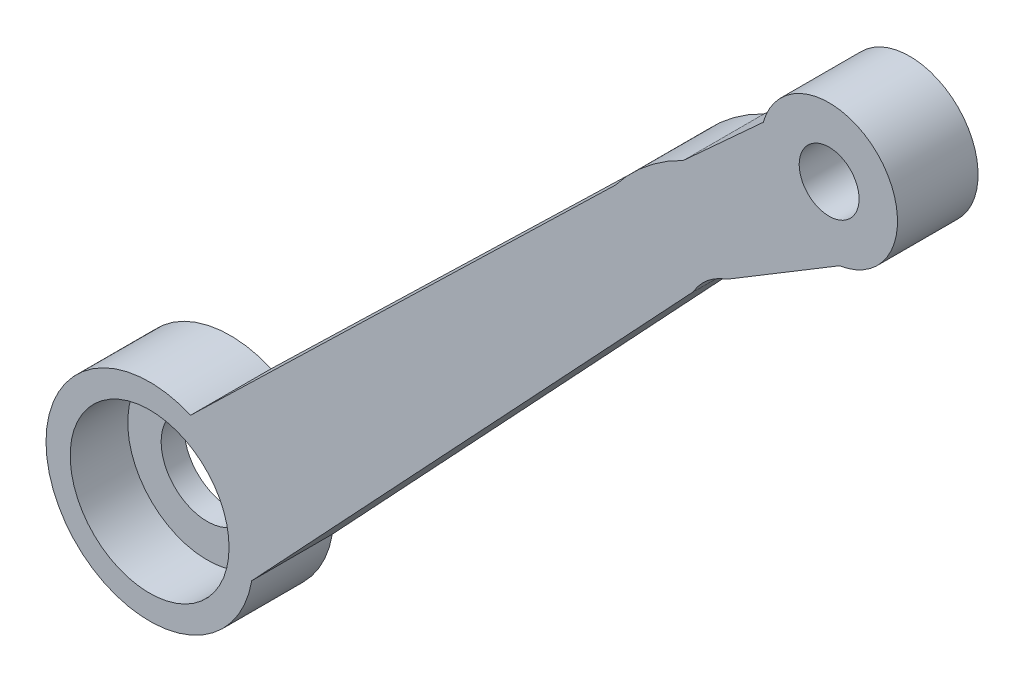
SolidWorks part; units mm, degrees
ref_plane "Front Plane" through (0, 0, 0) normal (0, 0, 1) x (1, 0, 0)
ref_plane "Top Plane" through (0, 0, 0) normal (0, 1, 0) x (1, 0, 0)
ref_plane "Right Plane" through (0, 0, 0) normal (1, 0, 0) x (0, 0, -1)
sketch "Sketch1" plane through (0, 0, 0) normal (0, 0, 1) x (1, 0, 0)
  line L8 (-116.1165, -73.1162) -> (-77.7804, -32.2217)
  line L9 (-74.8335, -29.7976) -> (-65.0583, -23.8962)
  line L10 (-71.6872, -16.4176) -> (-78.6359, -22.7631)
  line L11 (-84.5297, -27.5637) -> (-121.4306, -63.3278)
  circle A0 centre (-65.9692, -18.0264) radius 2.6
  circle A1 centre (-124.987, -71.5953) radius 6.9
  arc A2 (-121.4306, -63.3278) -> (-116.1165, -73.1162) centre (-124.987, -71.5953) ccw
  arc A9 (-74.8335, -29.7976) -> (-77.7804, -32.2217) centre (-73.0977, -34.911) ccw
  arc A10 (-65.0583, -23.8962) -> (-71.6872, -16.4176) centre (-65.9692, -18.0264) ccw
  arc A11 (-78.6359, -22.7631) -> (-84.5297, -27.5637) centre (-71.4001, -37.665) ccw
  point P10 (-80.3373, -21.4949)
  point P13 (-87.0133, -26.9788)
  point P15 (-121.4306, -63.3278)
  point P16 (-116.1165, -73.1162)
  point P18 (-74.8335, -29.7976)
  point P19 (-77.7804, -32.2217)
  point P20 (-84.5297, -27.5637)
  point P21 (-78.6359, -22.7631)
extrude "Boss-Extrude1" add sketch "Sketch1" along normal blind 5
sketch "Sketch2" plane through (0, 0, 0) normal (0, 0, -1) x (-1, 0, 0)
  line L4 (121.4306, -63.3278) -> (84.5297, -27.5637)
  line L5 (78.6359, -22.7631) -> (71.6872, -16.4176)
  line L6 (65.0583, -23.8962) -> (74.8335, -29.7976)
  line L7 (77.7804, -32.2217) -> (116.1165, -73.1162)
  line L8 (121.4306, -63.3278) -> (84.5297, -27.5637)
  line L9 (78.6359, -22.7631) -> (71.6872, -16.4176)
  line L10 (65.0583, -23.8962) -> (74.8335, -29.7976)
  line L11 (77.7804, -32.2217) -> (116.1165, -73.1162)
  circle A0 centre (124.987, -71.5953) radius 4
  circle A1 centre (65.9692, -18.0264) radius 2.6
  arc A4 (116.1165, -73.1162) -> (121.4306, -63.3278) centre (124.987, -71.5953) ccw
  arc A5 (84.5297, -27.5637) -> (78.6359, -22.7631) centre (71.4001, -37.665) ccw
  arc A6 (71.6872, -16.4176) -> (65.0583, -23.8962) centre (65.9692, -18.0264) ccw
  arc A7 (77.7804, -32.2217) -> (74.8335, -29.7976) centre (73.0977, -34.911) ccw
  arc A8 (116.1165, -73.1162) -> (121.4306, -63.3278) centre (124.987, -71.5953) ccw
  arc A9 (84.5297, -27.5637) -> (78.6359, -22.7631) centre (71.4001, -37.665) ccw
  arc A10 (71.6872, -16.4176) -> (65.0583, -23.8962) centre (65.9692, -18.0264) ccw
  arc A11 (77.7804, -32.2217) -> (74.8335, -29.7976) centre (73.0977, -34.911) ccw
  dimension "D2" = 8
  dimension "D3" = 5.2
  dimension "D1" = 0
extrude "Boss-Extrude2" add sketch "Sketch2" along normal blind 2
